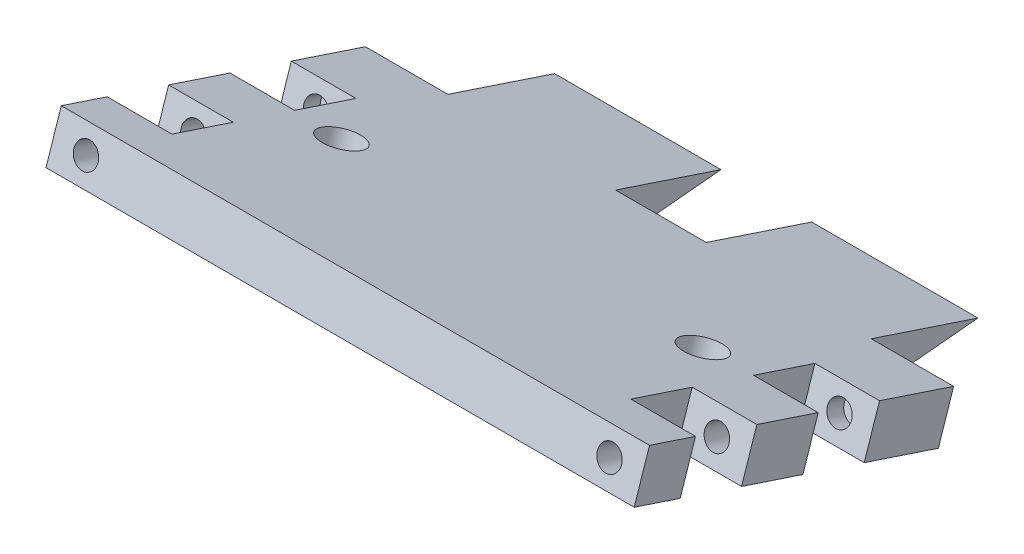
SolidWorks part; units mm, degrees
ref_plane "Front Plane" through (0, 0, 0) normal (0, 0, 1) x (1, 0, 0)
ref_plane "Top Plane" through (0, 0, 0) normal (0, 1, 0) x (1, 0, 0)
ref_plane "Right Plane" through (0, 0, 0) normal (1, 0, 0) x (0, 0, -1)
sketch "Sketch2" plane through (0, 0, 0) normal (1, 0, 0) x (0, 0, -1)
  line L0 (-113.4962, -18.2671) -> (-65.3752, -34.2461)
  line L1 (-65.3752, -34.2461) -> (-46.5005, -32.4845)
  line L3 (-111.0949, -11.0354) -> (-46.5005, -32.4845)
  line L4 (-113.4962, -18.2671) -> (-111.0949, -11.0354)
  dimension "D2" = 7.62
extrude "Frame" add sketch "Sketch2" along normal mid plane 92.456 separate body
sketch "Sketch20" plane through (0, -50.3976, 16.735) normal (0, -0.949, 0.3151) x (1, 0, 0)
  line L0 (54.6923, 94.3364) -> (36.068, 94.3364)
  line L1 (36.068, 94.3364) -> (36.068, 84.1764)
  line L2 (36.068, 84.1764) -> (48.8577, 84.1764)
  line L3 (48.8577, 84.1764) -> (48.8577, 74.0164)
  line L4 (48.8577, 74.0164) -> (36.068, 74.0164)
  line L5 (36.068, 74.0164) -> (36.068, 63.8564)
  line L6 (36.068, 63.8564) -> (53.6247, 63.8564)
  line L7 (53.6247, 63.8564) -> (54.6923, 94.3364)
  line L8 (0, 135.1129) -> (0, -20.6529) construction
  line L17 (46.228, 101.9564) -> (-46.228, 101.9564) construction
  line L18 (46.228, 101.9564) -> (46.228, 51.2518) construction
  line L23 (7.1294, 51.3536) -> (-7.1294, 51.3536)
  line L24 (57.5395, 51.5764) -> (57.5395, 27.2266)
  line L25 (7.1294, 27.2266) -> (-7.1294, 27.2266)
  line L26 (33.2714, 27.2266) -> (57.5395, 27.2266)
  line L27 (-33.2714, 27.2266) -> (-33.2714, 51.5764)
  line L28 (7.1294, 51.3536) -> (7.1294, 27.2266)
  line L29 (57.5395, 51.5764) -> (33.2714, 51.5764)
  line L30 (33.2714, 27.2266) -> (33.2714, 51.5764)
  line L31 (-57.5395, 51.5764) -> (-33.2714, 51.5764)
  line L32 (-7.1294, 51.3536) -> (-7.1294, 27.2266)
  line L33 (-33.2714, 27.2266) -> (-57.5395, 27.2266)
  line L34 (-57.5395, 51.5764) -> (-57.5395, 27.2266)
  line L35 (-53.6247, 63.8564) -> (-54.6923, 94.3364)
  line L36 (-36.068, 63.8564) -> (-53.6247, 63.8564)
  line L37 (-36.068, 74.0164) -> (-36.068, 63.8564)
  line L38 (-48.8577, 74.0164) -> (-36.068, 74.0164)
  line L39 (-48.8577, 84.1764) -> (-48.8577, 74.0164)
  line L40 (-36.068, 84.1764) -> (-48.8577, 84.1764)
  line L41 (-36.068, 94.3364) -> (-36.068, 84.1764)
  line L42 (-54.6923, 94.3364) -> (-36.068, 94.3364)
  circle A1 centre (-28.4072, 74.3339) radius 3.175
  circle A4 centre (28.4072, 74.3339) radius 3.175
  point P13 (0, 51.3536)
  point P25 (0, 27.2266)
  point P37 (0, 27.2266)
  point P39 (0, 51.3536)
  dimension "D1" = 7.62
  dimension "D2" = 10.16
  dimension "D3" = 10.16
extrude "Extrude25" cut sketch "Sketch20" against normal blind 12.7
sketch "Sketch34" plane through (0, 32.1304, 96.7613) normal (0, 0.3151, 0.949) x (1, 0, 0)
  line L0 (-41.1418, 38.6565) -> (-41.1418, -49.2934) construction
  line L1 (0, 48.2417) -> (0, -27.4221) construction
  line L2 (-46.228, -49.2934) -> (-41.1418, -49.2934) construction
  line L3 (-46.228, -45.4834) -> (-46.228, -53.1034) construction
  circle A0 centre (-41.1418, -49.2934) radius 1.905
  circle A1 centre (41.1418, -49.2934) radius 1.905
  dimension "D1" = 3.81
extrude "Extrude26" cut sketch "Sketch34" against normal blind 40.894
